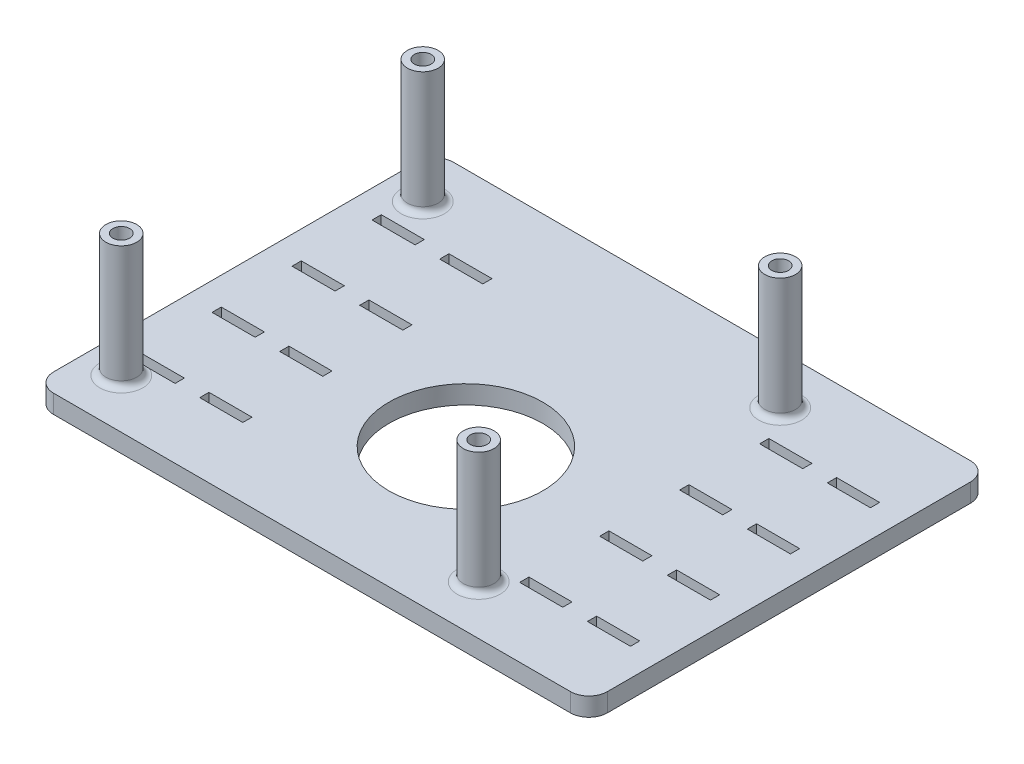
SolidWorks part; units mm, degrees
ref_plane "Front" through (0, 0, 0) normal (0, 0, 1) x (1, 0, 0)
ref_plane "Top" through (0, 0, 0) normal (0, 1, 0) x (1, 0, 0)
ref_plane "Right" through (0, 0, 0) normal (1, 0, 0) x (0, 0, -1)
sketch "Skizze1" plane through (0, 0, 0) normal (0, 1, 0) x (1, 0, 0)
  line L0 (-45, -32.5) -> (-45, 32.5)
  line L1 (-45, -32.5) -> (45, -32.5)
  line L2 (-45, 32.5) -> (45, 32.5)
  line L3 (45, -32.5) -> (45, 32.5)
  line L4 (-45, -32.5) -> (45, 32.5) construction
  line L5 (-45, 32.5) -> (45, -32.5) construction
  point P1 (0, 0)
  dimension "D1" = 90
  dimension "D2" = 65
extrude "Aufsatz-Linear austragen1" add sketch "Skizze1" along normal blind 3
sketch "Skizze3" plane through (0, 3, 0) normal (0, 1, 0) x (1, 0, 0)
  circle A0 centre (-39, 24.5) radius 2.5
  circle A1 centre (19.0855, 24.5) radius 2.5
  circle A2 centre (19.0855, -24.5) radius 2.5
  circle A3 centre (-39, -24.5) radius 2.5
  dimension "D1" = 5
extrude "Aufsatz-Linear austragen2" add sketch "Skizze3" along normal blind 20
sketch "Skizze4" plane through (0, 23, 0) normal (0, 1, 0) x (1, 0, 0)
  circle A0 centre (19.0855, 24.5) radius 1.3645 construction
  circle A3 centre (-39, 24.5) radius 1.3645 construction
  circle A4 centre (-39, -24.5) radius 1.3645 construction
  circle A5 centre (19.0855, -24.5) radius 1.3645 construction
  circle A6 centre (19.0855, 24.5) radius 1.3645
  circle A7 centre (-39, 24.5) radius 1.3645
  circle A8 centre (-39, -24.5) radius 1.3645
  circle A9 centre (19.0855, -24.5) radius 1.3645
extrude "Schnitt-Linear austragen2" cut sketch "Skizze4" against normal through all
fillet "Verrundung1" radius 3 4 edges at (45, 1.5, -32.5) (-45, 1.5, -32.5) (-45, 1.5, 32.5) (45, 1.5, 32.5)
fillet "Verrundung2" radius 1 4 edges at (-39, 3, 27) (19.0855, 3, 27) (19.0855, 3, -22) (-39, 3, -22)
sketch "Skizze5" plane through (0, 0, 0) normal (0, -1, 0) x (1, 0, 0)
  circle A0 centre (-1, 6.5) radius 12.5003
  circle A2 centre (-39, 24.5) radius 1.3645 construction
  dimension "D1" = 18
  dimension "D3" = 25.0007
  dimension "D2" = 38
extrude "Schnitt-Linear austragen3" cut sketch "Skizze5" against normal through all
sketch "Skizze6" plane through (0, 0, 0) normal (0, -1, 0) x (1, 0, 0)
  line L0 (-45, 20.5) -> (45, 20.5) construction
  line L1 (-40.5, 21.25) -> (-33.5, 21.25)
  line L2 (-40.5, 21.25) -> (-40.5, 19.75)
  line L3 (-40.5, 19.75) -> (-33.5, 19.75)
  line L4 (-33.5, 21.25) -> (-33.5, 19.75)
  line L5 (-37, 19.75) -> (-37, 21.25) construction
  line L6 (-40.5, 20.5) -> (-33.5, 20.5) construction
  line L7 (-29.5, 21.25) -> (-22.5, 21.25)
  line L8 (-29.5, 21.25) -> (-29.5, 19.75)
  line L9 (-29.5, 19.75) -> (-22.5, 19.75)
  line L10 (-22.5, 21.25) -> (-22.5, 19.75)
  line L11 (-26, 19.75) -> (-26, 21.25) construction
  line L12 (-29.5, 20.5) -> (-22.5, 20.5) construction
  line L13 (22.5, 21.25) -> (29.5, 21.25)
  line L14 (22.5, 21.25) -> (22.5, 19.75)
  line L15 (22.5, 19.75) -> (29.5, 19.75)
  line L16 (29.5, 21.25) -> (29.5, 19.75)
  line L17 (26, 19.75) -> (26, 21.25) construction
  line L18 (22.5, 20.5) -> (29.5, 20.5) construction
  line L19 (33.5, 21.25) -> (40.5, 21.25)
  line L20 (33.5, 21.25) -> (33.5, 19.75)
  line L21 (33.5, 19.75) -> (40.5, 19.75)
  line L22 (40.5, 21.25) -> (40.5, 19.75)
  line L23 (37, 19.75) -> (37, 21.25) construction
  line L24 (33.5, 20.5) -> (40.5, 20.5) construction
  line L25 (-45, -29.5) -> (-45, 29.5) construction
  line L26 (45, 29.5) -> (45, -29.5) construction
  line L27 (-42, 32.5) -> (42, 32.5) construction
  point P30 (-37.8884, 15.286)
  point P31 (-27.5235, 15.286)
  point P32 (23.0814, 15.286)
  point P33 (36.2335, 15.286)
  point P38 (37, 20.5)
  point P39 (-26.3604, 15.3023)
  point P72 (-37, 20.5)
  point P73 (-26, 20.5)
  point P82 (26, 20.5)
  dimension "D1" = 7
  dimension "D2" = 1.5
  dimension "D3" = 19
  dimension "D4" = 12
  dimension "D5" = 8
  dimension "D6" = 8
  dimension "D7" = 19
extrude "Schnitt-Linear austragen4" cut sketch "Skizze6" against normal through all
pattern_linear "Lineares Muster1" count 4 spacing 13 along (0, 0, -1) of "Schnitt-Linear austragen4"
